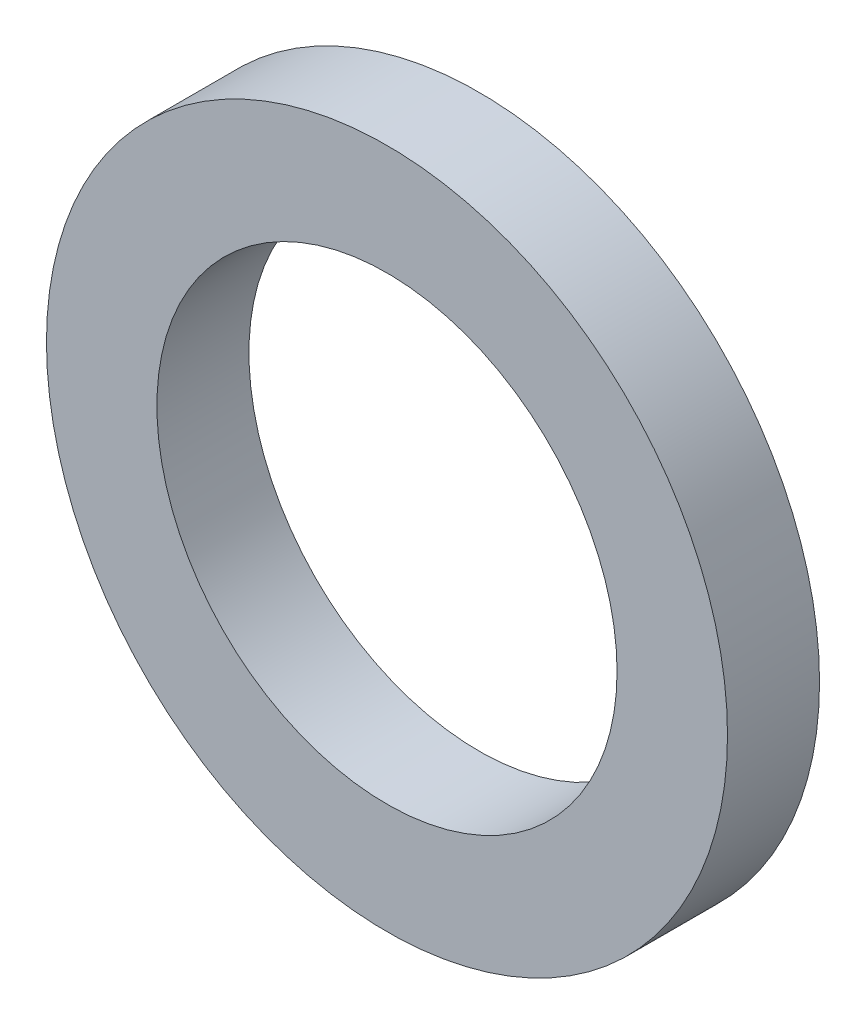
SolidWorks part; units mm, degrees
ref_plane "Спереди" through (0, 0, 0) normal (0, 0, 1) x (1, 0, 0)
ref_plane "Сверху" through (0, 0, 0) normal (0, 1, 0) x (1, 0, 0)
ref_plane "Справа" through (0, 0, 0) normal (1, 0, 0) x (0, 0, -1)
sketch "Эскиз1" plane through (0, 0, 0) normal (0, 0, 1) x (1, 0, 0)
  circle A0 centre (0, 0) radius 12.5
  circle A1 centre (0, 0) radius 18.5
  dimension "D1" = 37
  dimension "D2" = 25
extrude "Бобышка-Вытянуть1" add sketch "Эскиз1" along normal blind 5
